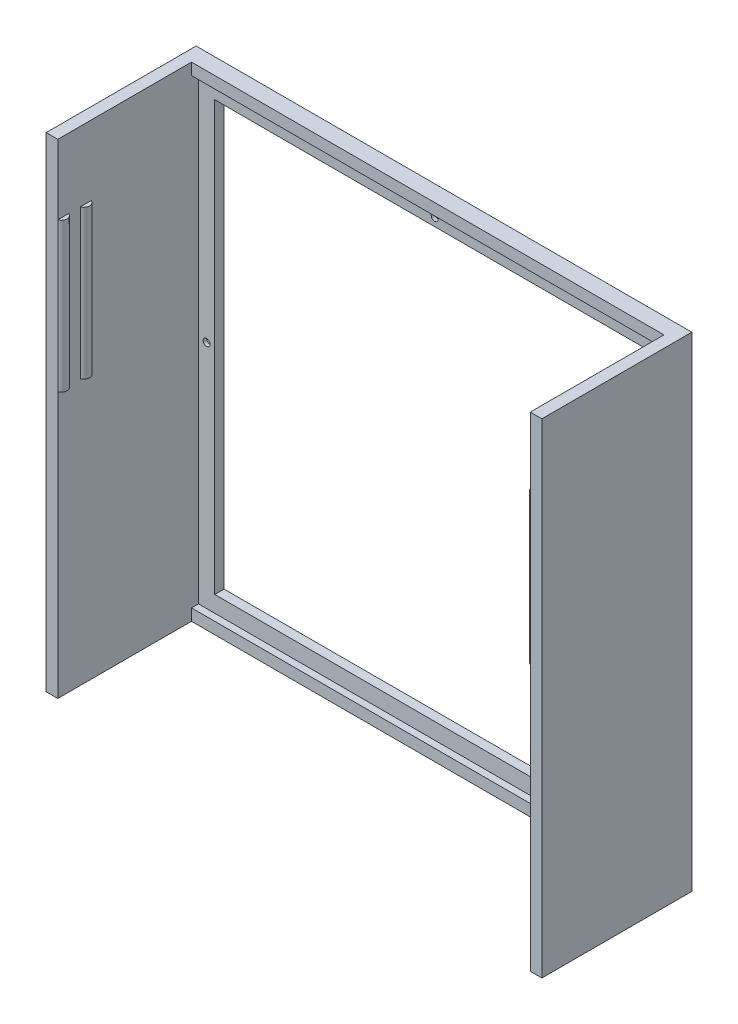
SolidWorks part; units mm, degrees
ref_plane "Front" through (0, 0, 0) normal (0, 0, 1) x (1, 0, 0)
ref_plane "Top" through (0, 0, 0) normal (0, 1, 0) x (1, 0, 0)
ref_plane "Right" through (0, 0, 0) normal (1, 0, 0) x (0, 0, -1)
sketch "Sketch1" plane through (0, 0, 0) normal (0, 0, 1) x (1, 0, 0)
  line L1 (-106.6, 104.14) -> (106.6, 104.14)
  line L2 (-106.6, 104.14) -> (-106.6, -104.14)
  line L3 (-106.6, -104.14) -> (106.6, -104.14)
  line L4 (106.6, 104.14) -> (106.6, -104.14)
  line L5 (-106.6, 104.14) -> (106.6, -104.14) construction
  line L6 (-106.6, -104.14) -> (106.6, 104.14) construction
  line L7 (-101.6, 99.14) -> (101.6, 99.14)
  line L8 (-101.6, 99.14) -> (-101.6, -99.14)
  line L9 (-101.6, -99.14) -> (101.6, -99.14)
  line L10 (101.6, 99.14) -> (101.6, -99.14)
  line L11 (-101.6, 99.14) -> (101.6, -99.14) construction
  line L12 (-101.6, -99.14) -> (101.6, 99.14) construction
  point P0 (0, 0)
  point P6 (0, 0)
  dimension "D1" = 208.28
  dimension "D2" = 213.2
  dimension "D3" = 5
  dimension "D4" = 5
extrude "Boss-Extrude1" add sketch "Sketch1" along normal blind 7
sketch "Sketch2" plane through (0, 0, 0) normal (0, 0, 1) x (1, 0, 0)
  line L0 (0, -3.85) -> (0, 3.85) construction
  line L1 (-101.6, -99.14) -> (101.6, -99.14)
  line L2 (-101.6, -99.14) -> (-101.6, 99.14)
  line L3 (-101.6, 99.14) -> (101.6, 99.14)
  line L4 (101.6, -99.14) -> (101.6, 99.14)
  line L5 (-101.6, -99.14) -> (101.6, 99.14) construction
  line L6 (-101.6, 99.14) -> (101.6, -99.14) construction
  line L7 (-94.6, -92.14) -> (94.6, -92.14)
  line L8 (-94.6, -92.14) -> (-94.6, 92.14)
  line L9 (-94.6, 92.14) -> (94.6, 92.14)
  line L10 (94.6, -92.14) -> (94.6, 92.14)
  line L11 (-94.6, -92.14) -> (94.6, 92.14) construction
  line L12 (-94.6, 92.14) -> (94.6, -92.14) construction
  line L13 (3.85, 0) -> (-3.85, 0) construction
  circle A0 centre (0, 95.64) radius 1.5
  circle A1 centre (-98.1, 0) radius 1.5
  circle A2 centre (98.1, 0) radius 1.5
  point P0 (0, 0)
  point P7 (0, 0)
  dimension "D4" = 3
  dimension "D1" = 7
  dimension "D2" = 7
  dimension "D3" = 3.5
  dimension "D5" = 3.5
extrude "Boss-Extrude2" add sketch "Sketch2" along normal blind 4
sketch "Sketch3" plane through (0, 0, 7) normal (0, 0, 1) x (1, 0, 0)
  line L0 (-101.6, 99.14) -> (-101.6, -99.14) construction
  line L1 (-106.6, -104.14) -> (106.6, -104.14)
  line L2 (-106.6, -104.14) -> (-106.6, 104.14)
  line L3 (-106.6, 104.14) -> (106.6, 104.14)
  line L4 (106.6, -104.14) -> (106.6, 104.14)
  line L5 (-106.6, -104.14) -> (106.6, 104.14) construction
  line L6 (-106.6, 104.14) -> (106.6, -104.14) construction
  line L7 (-106.6, 104.14) -> (-101.6, 104.14)
  line L8 (-106.6, 104.14) -> (-106.6, -104.14)
  line L9 (-106.6, -104.14) -> (-101.6, -104.14)
  line L10 (-101.6, 104.14) -> (-101.6, -104.14)
  line L11 (0, -3.85) -> (0, 3.85) construction
  line L12 (106.6, -104.14) -> (101.6, -104.14)
  line L13 (101.6, 104.14) -> (101.6, -104.14)
  line L14 (106.6, 104.14) -> (101.6, 104.14)
  line L15 (106.6, 104.14) -> (106.6, -104.14)
  point P0 (0, 0)
  line M9 (106.6, -104.14) -> (106.6, 104.14)
  line M10 (106.6, 104.14) -> (-106.6, 104.14)
  line M11 (-106.6, 104.14) -> (-106.6, -104.14)
  line M12 (-106.6, -104.14) -> (106.6, -104.14)
  line M14 (101.6, 99.14) -> (101.6, -99.14)
  line M16 (-101.6, -99.14) -> (-101.6, 99.14)
extrude "Boss-Extrude3" add sketch "Sketch3" along normal blind 57.5 contours L10 L3 M11 M12 M16 | L13 M10 M14 M12 M9
sketch "Sketch4" plane through (0, 104.14, 0) normal (0, 1, 0) x (1, 0, 0)
  line L0 (-101.6, -64.5) -> (-101.6, -7) construction
  line L1 (-101.6, -59.8) -> (-101.6, -64.5)
  line L2 (0, -3.85) -> (0, 3.85) construction
  line L3 (101.6, -59.8) -> (101.6, -64.5)
  line L4 (-101.6, -50.1) -> (-101.6, -54.8)
  line L5 (101.6, -50.1) -> (101.6, -54.8)
  arc A0 (-101.6, -64.5) -> (-101.6, -59.8) centre (-102.4529, -62.15) ccw
  arc A1 (101.6, -64.5) -> (101.6, -59.8) centre (102.4529, -62.15) cw
  arc A2 (-101.6, -54.8) -> (-101.6, -50.1) centre (-102.4529, -52.45) ccw
  arc A3 (101.6, -54.8) -> (101.6, -50.1) centre (102.4529, -52.45) cw
  dimension "D2" = 2.5
  dimension "D1" = 4.7
  dimension "D3" = 2
extrude "Boss-Extrude4" add sketch "Sketch4" against normal blind 64 from offset 30 offset against normal yes
sketch "Sketch5" plane through (0, 0, 4) normal (0, 0, 1) x (1, 0, 0)
  line L0 (0, -3.85) -> (0, 3.85) construction
  line L1 (-95.325, -1.6021) -> (-95.325, 1.6021)
  line L2 (-95.325, 1.6021) -> (-98.1, 3.2043)
  line L3 (-98.1, 3.2043) -> (-100.875, 1.6021)
  line L4 (-100.875, 1.6021) -> (-100.875, -1.6021)
  line L5 (-100.875, -1.6021) -> (-98.1, -3.2043)
  line L6 (-98.1, -3.2043) -> (-95.325, -1.6021)
  line L7 (98.1, -3.2043) -> (95.325, -1.6021)
  line L8 (100.875, -1.6021) -> (98.1, -3.2043)
  line L9 (100.875, 1.6021) -> (100.875, -1.6021)
  line L10 (98.1, 3.2043) -> (100.875, 1.6021)
  line L11 (95.325, 1.6021) -> (98.1, 3.2043)
  line L12 (95.325, -1.6021) -> (95.325, 1.6021)
  line L14 (1.6021, 92.865) -> (3.2043, 95.64)
  line L15 (3.2043, 95.64) -> (1.6021, 98.415)
  line L16 (1.6021, 98.415) -> (-1.6021, 98.415)
  line L17 (-1.6021, 98.415) -> (-3.2043, 95.64)
  line L18 (-3.2043, 95.64) -> (-1.6021, 92.865)
  line L19 (-1.6021, 92.865) -> (1.6021, 92.865)
  circle A0 centre (-98.1, 0) radius 2.775 construction
  circle A1 centre (98.1, 0) radius 2.775 construction
  circle A2 centre (0, 95.64) radius 2.775 construction
  dimension "D1" = 5.55
  dimension "D2" = 5.55
extrude "Cut-Extrude1" cut sketch "Sketch5" along normal blind 2.5 from surface at -4 starting at face at (0, 0, 0)
